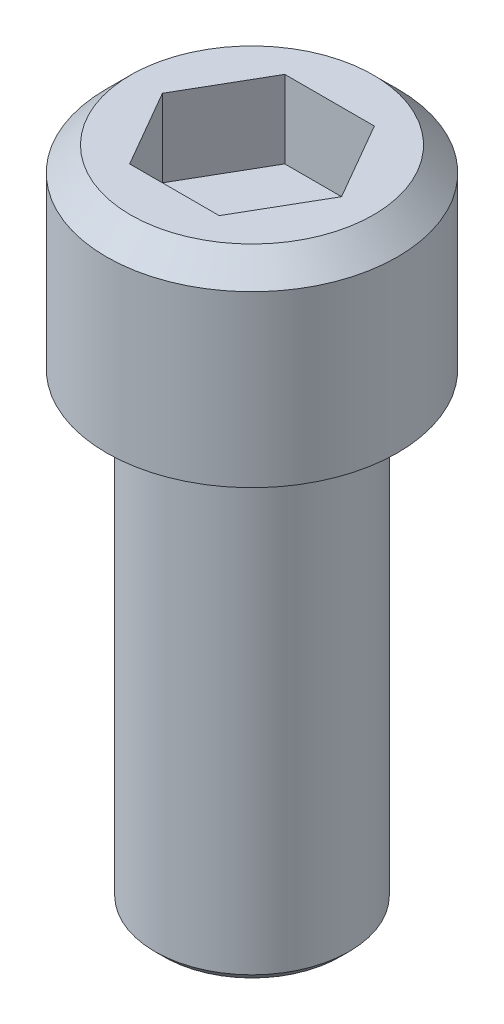
SolidWorks part; units mm, degrees
material "Alloy Steel"
ref_plane "Plane1" through (0, 0, 0) normal (0, 0, 1) x (1, 0, 0)
ref_plane "Plane2" through (0, 0, 0) normal (0, 1, 0) x (1, 0, 0)
ref_plane "Plane3" through (0, 0, 0) normal (1, 0, 0) x (0, 0, -1)
other "Configuration Table"
sketch "Sketch1" plane through (0, 0, 0) normal (0, 0, 1) x (1, 0, 0)
  line L0 (0, 0) -> (0, 43.6223) construction
  line L1 (7.9502, 0) -> (11.9126, 0)
  line L2 (11.9126, 0) -> (11.9126, 15.875)
  line L3 (11.9126, 15.875) -> (0, 15.875)
  line L4 (0, 15.875) -> (0, -38.1)
  line L5 (0, -38.1) -> (7.9502, -38.1)
  line L6 (7.9502, -38.1) -> (7.9502, 0)
  line L7 (50, 0) -> (-50, 0) construction
  dimension "D1" = 23.8252
  dimension "D2" = 15.9004
  dimension "D3" = 15.875
  dimension "D4" = 38.1
revolve "Base-Revolve" add sketch "Sketch1" angle 360 about L0
sketch "Sketch2" plane through (0, 15.875, 0) normal (0, 1, 0) x (-1, 0, 0)
  line L0 (3.6662, -6.35) -> (-3.6662, -6.35)
  line L1 (-7.3323, 0) -> (-3.6662, -6.35)
  line L2 (0, 0) -> (0, -6.35) construction
  line L3 (0, 0) -> (-7.3323, 0) construction
  line L4 (7.3323, 0) -> (3.6662, -6.35)
  line L5 (7.3323, 0) -> (3.6662, 6.35)
  line L6 (-7.3323, 0) -> (-3.6662, 6.35)
  line L7 (3.6662, 6.35) -> (-3.6662, 6.35)
  circle A0 centre (0, 0) radius 6.35 construction
  point P12 (0, -6.35)
  point P14 (0, 6.35)
  dimension "D2" = 12.7
extrude "Cut-Extrude1" cut sketch "Sketch2" against normal blind 6.35
chamfer "Chamfer1" distance 1.9812 angle 45 1 edges at (0, 15.875, -11.9126)
chamfer "Chamfer2" distance 0.762 angle 45 1 edges at (0, -38.1, -7.9502)
